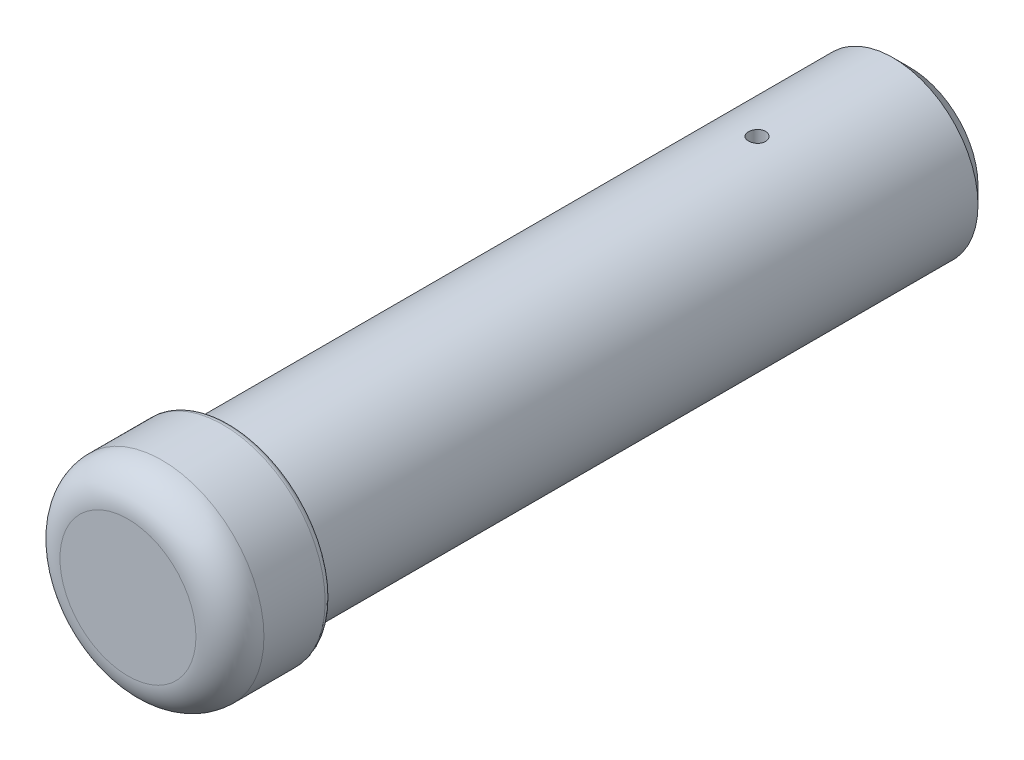
SolidWorks part; units mm, degrees
material "1.1191 (C45E)"
ref_plane "Front Plane" through (0, 0, 0) normal (0, 0, 1) x (1, 0, 0)
ref_plane "Top Plane" through (0, 0, 0) normal (0, 1, 0) x (1, 0, 0)
ref_plane "Right Plane" through (0, 0, 0) normal (1, 0, 0) x (0, 0, -1)
sketch "Sketch1" plane through (0, 0, 0) normal (0, 0, 1) x (1, 0, 0)
  circle A0 centre (0, 0) radius 25
  dimension "D1" = 50
extrude "Boss-Extrude1" add sketch "Sketch1" along normal blind 200
sketch "Sketch2" plane through (0, 0, 200) normal (0, 0, 1) x (1, 0, 0)
  circle A0 centre (0, 0) radius 30
  dimension "D1" = 60
extrude "Boss-Extrude2" add sketch "Sketch2" along normal blind 30
fillet "Fillet1" radius 10 1 edges at (30, 0, 230)
fillet "Fillet2" radius 2 2 edges at (30, 0, 200) (25, 0, 200)
chamfer "Chamfer1" distance 5 angle 45 1 edges at (25, 0, 0)
sketch "Sketch3" plane through (0, 0, 0) normal (0, 1, 0) x (1, 0, 0)
  line L0 (25, -5) -> (-25, -5) construction
  circle A0 centre (0, -45) radius 2.5
  dimension "D1" = 5
  dimension "D2" = 40
extrude "Cut-Extrude1" cut sketch "Sketch3" against normal through all both and the other way through all
